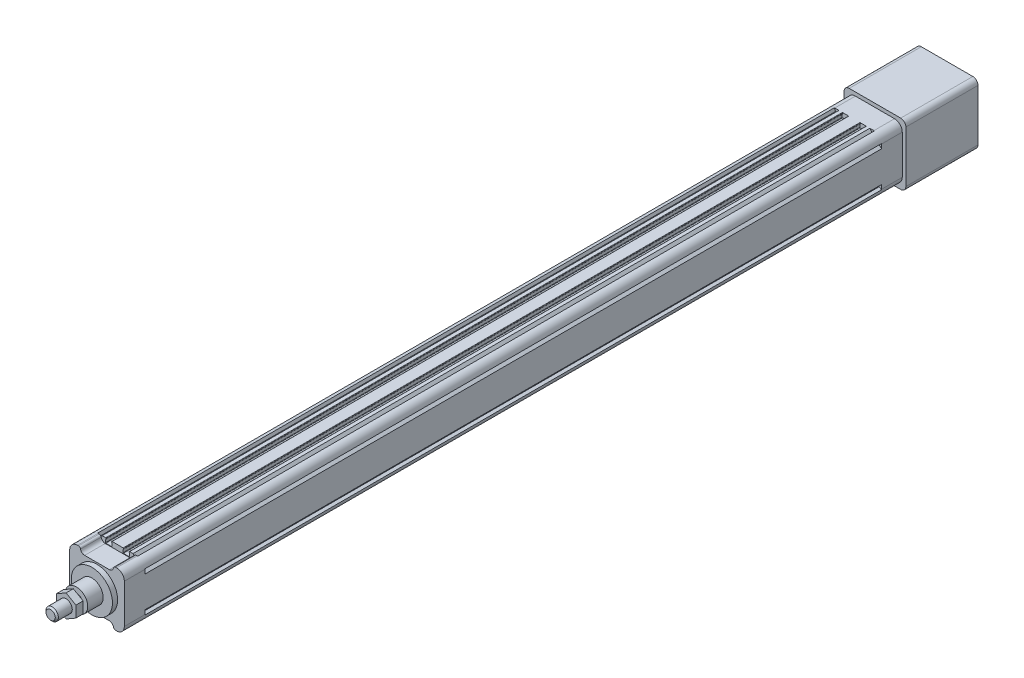
SolidWorks part; units mm, degrees
ref_plane "Front" through (0, 0, 0) normal (0, 0, 1) x (1, 0, 0)
ref_plane "Top" through (0, 0, 0) normal (0, 1, 0) x (1, 0, 0)
ref_plane "Right" through (0, 0, 0) normal (1, 0, 0) x (0, 0, -1)
sketch "草图1" plane through (0, 0, 0) normal (0, 0, 1) x (1, 0, 0)
  line L0 (19.7737, 3) -> (23.3, 3)
  line L1 (23.3, 3) -> (23.3, -3)
  line L2 (23.3, -3) -> (19.7737, -3)
  line L3 (-19.7737, -3) -> (-23.3, -3)
  line L4 (-23.3, -3) -> (-23.3, 3)
  line L5 (-23.3, 3) -> (-19.7737, 3)
  line L6 (-18.2, 24) -> (-19.4434, 26.4869)
  line L7 (-26.4869, 19.4434) -> (-24, 18.2)
  line L8 (-24, 18.2) -> (-24, 17.1)
  line L9 (-24, 17.1) -> (-26.5, 15)
  line L10 (-26.5, 15) -> (-26.5, -15)
  line L11 (-26.5, -15) -> (-24, -17.1)
  line L12 (-24, -17.1) -> (-24, -18.2)
  line L13 (-24, -18.2) -> (-26.4869, -19.4434)
  line L14 (-19.4434, -26.4869) -> (-18.2, -24)
  line L15 (-18.2, -24) -> (-17.1, -24)
  line L16 (-17.1, -24) -> (-15, -26.5)
  line L17 (-15, -26.5) -> (-11.65, -26.5)
  line L18 (-11.25, -26.1) -> (-11.25, -25.6)
  line L19 (-11.65, -25.2) -> (-11.75, -25.2)
  line L20 (-11.75, -25.2) -> (-11.75, -22.4)
  line L21 (-11.35, -22) -> (-5.65, -22)
  line L22 (-5.25, -22.4) -> (-5.25, -25.2)
  line L23 (-5.25, -25.2) -> (-5.35, -25.2)
  line L24 (-5.75, -25.6) -> (-5.75, -26.1)
  line L25 (-5.35, -26.5) -> (5.35, -26.5)
  line L26 (5.75, -26.1) -> (5.75, -25.6)
  line L27 (5.35, -25.2) -> (5.25, -25.2)
  line L28 (5.25, -25.2) -> (5.25, -22.4)
  line L29 (5.65, -22) -> (11.35, -22)
  line L30 (11.75, -22.4) -> (11.75, -25.2)
  line L31 (11.75, -25.2) -> (11.65, -25.2)
  line L32 (11.25, -25.6) -> (11.25, -26.1)
  line L33 (11.65, -26.5) -> (15, -26.5)
  line L34 (15, -26.5) -> (17.1, -24)
  line L35 (17.1, -24) -> (18.2, -24)
  line L36 (18.2, -24) -> (19.4434, -26.4869)
  line L37 (26.4869, -19.4434) -> (24, -18.2)
  line L38 (24, -18.2) -> (24, -17.1)
  line L39 (24, -17.1) -> (26.5, -15)
  line L40 (26.5, -15) -> (26.5, 15)
  line L41 (26.5, 15) -> (24, 17.1)
  line L42 (24, 17.1) -> (24, 18.2)
  line L43 (24, 18.2) -> (26.4869, 19.4434)
  line L44 (19.4434, 26.4869) -> (18.2, 24)
  line L45 (18.2, 24) -> (17.1, 24)
  line L46 (17.1, 24) -> (15, 26.5)
  line L47 (15, 26.5) -> (11.65, 26.5)
  line L48 (11.25, 26.1) -> (11.25, 25.6)
  line L49 (11.65, 25.2) -> (11.75, 25.2)
  line L50 (11.75, 25.2) -> (11.75, 22.4)
  line L51 (11.35, 22) -> (5.65, 22)
  line L52 (5.25, 22.4) -> (5.25, 25.2)
  line L53 (5.25, 25.2) -> (5.35, 25.2)
  line L54 (5.75, 25.6) -> (5.75, 26.1)
  line L55 (5.35, 26.5) -> (-5.35, 26.5)
  line L56 (-5.75, 26.1) -> (-5.75, 25.6)
  line L57 (-5.35, 25.2) -> (-5.25, 25.2)
  line L58 (-5.25, 25.2) -> (-5.25, 22.4)
  line L59 (-5.65, 22) -> (-11.35, 22)
  line L60 (-11.75, 22.4) -> (-11.75, 25.2)
  line L61 (-11.75, 25.2) -> (-11.65, 25.2)
  line L62 (-11.25, 25.6) -> (-11.25, 26.1)
  line L63 (-11.65, 26.5) -> (-15, 26.5)
  line L64 (-15, 26.5) -> (-17.1, 24)
  line L65 (-17.1, 24) -> (-18.2, 24)
  arc A0 (19.7737, 3) -> (-19.7737, 3) centre (0, 0) ccw
  arc A1 (-19.7737, -3) -> (19.7737, -3) centre (0, 0) ccw
  circle A2 centre (19, 19) radius 2.1
  circle A3 centre (19, -19) radius 2.1
  circle A4 centre (-19, -19) radius 2.1
  circle A5 centre (-19, 19) radius 2.1
  arc A6 (-19.4434, 26.4869) -> (-26.4869, 19.4434) centre (-19, 19) ccw
  arc A7 (-26.4869, -19.4434) -> (-19.4434, -26.4869) centre (-19, -19) ccw
  arc A8 (-11.65, -26.5) -> (-11.25, -26.1) centre (-11.65, -26.1) ccw
  arc A9 (-11.25, -25.6) -> (-11.65, -25.2) centre (-11.65, -25.6) ccw
  arc A10 (-11.35, -22) -> (-11.75, -22.4) centre (-11.35, -22.4) ccw
  arc A11 (-5.25, -22.4) -> (-5.65, -22) centre (-5.65, -22.4) ccw
  arc A12 (-5.35, -25.2) -> (-5.75, -25.6) centre (-5.35, -25.6) ccw
  arc A13 (-5.75, -26.1) -> (-5.35, -26.5) centre (-5.35, -26.1) ccw
  arc A14 (5.35, -26.5) -> (5.75, -26.1) centre (5.35, -26.1) ccw
  arc A15 (5.75, -25.6) -> (5.35, -25.2) centre (5.35, -25.6) ccw
  arc A16 (5.65, -22) -> (5.25, -22.4) centre (5.65, -22.4) ccw
  arc A17 (11.75, -22.4) -> (11.35, -22) centre (11.35, -22.4) ccw
  arc A18 (11.65, -25.2) -> (11.25, -25.6) centre (11.65, -25.6) ccw
  arc A19 (11.25, -26.1) -> (11.65, -26.5) centre (11.65, -26.1) ccw
  arc A20 (19.4434, -26.4869) -> (26.4869, -19.4434) centre (19, -19) ccw
  arc A21 (26.4869, 19.4434) -> (19.4434, 26.4869) centre (19, 19) ccw
  arc A22 (11.65, 26.5) -> (11.25, 26.1) centre (11.65, 26.1) ccw
  arc A23 (11.25, 25.6) -> (11.65, 25.2) centre (11.65, 25.6) ccw
  arc A24 (11.35, 22) -> (11.75, 22.4) centre (11.35, 22.4) ccw
  arc A25 (5.25, 22.4) -> (5.65, 22) centre (5.65, 22.4) ccw
  arc A26 (5.35, 25.2) -> (5.75, 25.6) centre (5.35, 25.6) ccw
  arc A27 (5.75, 26.1) -> (5.35, 26.5) centre (5.35, 26.1) ccw
  arc A28 (-5.35, 26.5) -> (-5.75, 26.1) centre (-5.35, 26.1) ccw
  arc A29 (-5.75, 25.6) -> (-5.35, 25.2) centre (-5.35, 25.6) ccw
  arc A30 (-5.65, 22) -> (-5.25, 22.4) centre (-5.65, 22.4) ccw
  arc A31 (-11.75, 22.4) -> (-11.35, 22) centre (-11.35, 22.4) ccw
  arc A32 (-11.65, 25.2) -> (-11.25, 25.6) centre (-11.65, 25.6) ccw
  arc A33 (-11.25, 26.1) -> (-11.65, 26.5) centre (-11.65, 26.1) ccw
extrude "凸台-拉伸1" add sketch "草图1" along normal blind 715
sketch "草图6" plane through (0, 0, 715) normal (0, 0, 1) x (1, 0, 0)
  line L0 (0, 0) -> (19, 0) construction
  line L2 (-26.5, -19) -> (-26.5, 19)
  line L3 (-19, 26.5) -> (-17.9161, 26.5)
  line L4 (26.5, -19) -> (26.5, 19)
  line L5 (-26.5, -26.5) -> (26.5, 26.5) construction
  line L6 (-26.5, 26.5) -> (26.5, -26.5) construction
  line L7 (-12, 21.5) -> (12, 21.5)
  line L9 (19, 26.5) -> (17.9161, 26.5)
  line L10 (19, -26.5) -> (17.9161, -26.5)
  line L11 (-12, -21.5) -> (12, -21.5)
  line L12 (-19, -26.5) -> (-17.9161, -26.5)
  arc A0 (12, 21.5) -> (15.9441, 24.8333) centre (12, 25.5) ccw
  arc A1 (-15.9441, 24.8333) -> (-12, 21.5) centre (-12, 25.5) ccw
  arc A2 (-15.9441, 24.8333) -> (-17.9161, 26.5) centre (-17.9161, 24.5) ccw
  arc A3 (15.9441, 24.8333) -> (17.9161, 26.5) centre (17.9161, 24.5) cw
  arc A4 (-26.5, -19) -> (-19, -26.5) centre (-19, -19) ccw
  arc A5 (19, -26.5) -> (26.5, -19) centre (19, -19) ccw
  arc A6 (26.5, 19) -> (19, 26.5) centre (19, 19) ccw
  arc A7 (-26.5, 19) -> (-19, 26.5) centre (-19, 19) cw
  arc A8 (15.9441, -24.8333) -> (17.9161, -26.5) centre (17.9161, -24.5) ccw
  arc A9 (12, -21.5) -> (15.9441, -24.8333) centre (12, -25.5) cw
  arc A10 (-15.9441, -24.8333) -> (-12, -21.5) centre (-12, -25.5) cw
  arc A11 (-15.9441, -24.8333) -> (-17.9161, -26.5) centre (-17.9161, -24.5) cw
  point P0 (0, 0)
  point P9 (0, 21.5)
  point P13 (20, 20.8461)
  point P16 (-12, 20.8461)
  dimension "D5" = 4
  dimension "D6" = 2
  dimension "D7" = 2
  dimension "D9" = 7.5
  dimension "D1" = 53
  dimension "D2" = 53
  dimension "D3" = 26.5
  dimension "D4" = 24
  dimension "D8" = 5
extrude "凸台-拉伸2" add sketch "草图6" along normal blind 20
sketch "草图7" plane through (0, 0, 735) normal (0, 0, 1) x (1, 0, 0)
  circle A0 centre (0, 0) radius 20
  dimension "D1" = 40
extrude "凸台-拉伸3" add sketch "草图7" along normal blind 5
sketch "草图9" plane through (0, 0, 740) normal (0, 0, 1) x (1, 0, 0)
  circle A0 centre (0, 0) radius 11
  dimension "D1" = 22
extrude "凸台-拉伸4" add sketch "草图9" along normal blind 15
sketch "草图10" plane through (0, 0, 755) normal (0, 0, 1) x (1, 0, 0)
  circle A0 centre (0, 0) radius 6
  dimension "D1" = 12
extrude "凸台-拉伸5" add sketch "草图10" along normal blind 25
sketch "草图11" plane through (0, 0, 0) normal (0, 0, -1) x (-1, 0, 0)
  line L1 (-19, -26.5) -> (19, -26.5)
  line L2 (-26.5, -19) -> (-26.5, 19)
  line L3 (-19, 26.5) -> (19, 26.5)
  line L4 (26.5, -19) -> (26.5, 19)
  line L5 (-26.5, -26.5) -> (26.5, 26.5) construction
  line L6 (-26.5, 26.5) -> (26.5, -26.5) construction
  arc A0 (-26.5, -19) -> (-19, -26.5) centre (-19, -19) ccw
  arc A1 (19, -26.5) -> (26.5, -19) centre (19, -19) ccw
  arc A2 (26.5, 19) -> (19, 26.5) centre (19, 19) ccw
  arc A3 (-26.5, 19) -> (-19, 26.5) centre (-19, 19) cw
  point P0 (0, 0)
  dimension "D3" = 7.5
  dimension "D1" = 53
  dimension "D2" = 53
extrude "凸台-拉伸6" add sketch "草图11" along normal blind 20
sketch "草图12" plane through (0, 0, -20) normal (0, 0, -1) x (-1, 0, 0)
  line L1 (-25, -30) -> (25, -30)
  line L2 (-30, -25) -> (-30, 25)
  line L3 (-25, 30) -> (25, 30)
  line L4 (30, -25) -> (30, 25)
  line L5 (-30, -30) -> (30, 30) construction
  line L6 (-30, 30) -> (30, -30) construction
  arc A0 (-30, -25) -> (-25, -30) centre (-25, -25) ccw
  arc A1 (25, -30) -> (30, -25) centre (25, -25) ccw
  arc A2 (30, 25) -> (25, 30) centre (25, 25) ccw
  arc A3 (-30, 25) -> (-25, 30) centre (-25, 25) cw
  point P0 (0, 0)
  dimension "D3" = 5
  dimension "D1" = 60
  dimension "D2" = 60
extrude "凸台-拉伸7" add sketch "草图12" along normal blind 70
sketch "草图14" plane through (0, 0, -90) normal (0, 0, -1) x (-1, 0, 0)
  circle A0 centre (0, 0) radius 19
  dimension "D1" = 38
extrude "切除-拉伸2" cut sketch "草图14" against normal blind 70
hole_wizard "M6 螺纹孔1" positions "草图15" profile "草图16" tap size "M6" standard "GB"
sketch "草图15" plane through (-26.5, 0, 0) normal (-1, 0, 0) x (0, 0, 1)
  line L0 (-20, -25) -> (-20, 25) construction
  line L1 (735, 19) -> (735, -19) construction
  point P0 (725, 11)
  point P2 (725, -11)
  point P4 (-10, 11)
  point P6 (-10, -11)
  dimension "D1" = 10
  dimension "D2" = 10
  dimension "D3" = 11
  dimension "D4" = 11
  dimension "D5" = 10
  dimension "D6" = 10
  dimension "D7" = 22
  dimension "D8" = 11
sketch "草图16" plane through (-26.5, 11, 725) normal (0, 1, 0) x (0, 0, 1)
  line L0 (0, 0) -> (0, 16.5022)
  line L1 (0, 16.5022) -> (2.5, 15)
  line L2 (2.5, 15) -> (2.5, 0)
  line L5 (2.5, 0) -> (0, 0)
  line L10 (0, 16.5022) -> (-2.5, 15) construction
  line L11 (0, -6.35) -> (0, 107.95) construction
  dimension "螺纹孔钻头直径" = 5
  dimension "螺纹孔钻头深度" = 15
  dimension "导头角度" = 118
cosmetic thread "孔螺蚊线4" parameters "D1"=12, "D2"=6
cosmetic thread "孔螺蚊线5" parameters "D1"=12, "D2"=6
cosmetic thread "孔螺蚊线6" parameters "D1"=12, "D2"=6
cosmetic thread "孔螺蚊线7" parameters "D1"=12, "D2"=6
chamfer "倒角1" distance 1.5 angle 45 1 edges at (6, 0, 780)
sketch "草图17" plane through (0, 0, 755) normal (0, 0, 1) x (1, 0, 0)
  line L1 (0, 10.9697) -> (-9.5, 5.4848)
  line L2 (-9.5, 5.4848) -> (-9.5, -5.4848)
  line L3 (-9.5, -5.4848) -> (0, -10.9697)
  line L4 (0, -10.9697) -> (9.5, -5.4848)
  line L5 (9.5, -5.4848) -> (9.5, 5.4848)
  line L6 (9.5, 5.4848) -> (0, 10.9697)
  circle A0 centre (0, 0) radius 9.5 construction
  dimension "D1" = 19
extrude "凸台-拉伸8" add sketch "草图17" along normal blind 7 from offset 3
